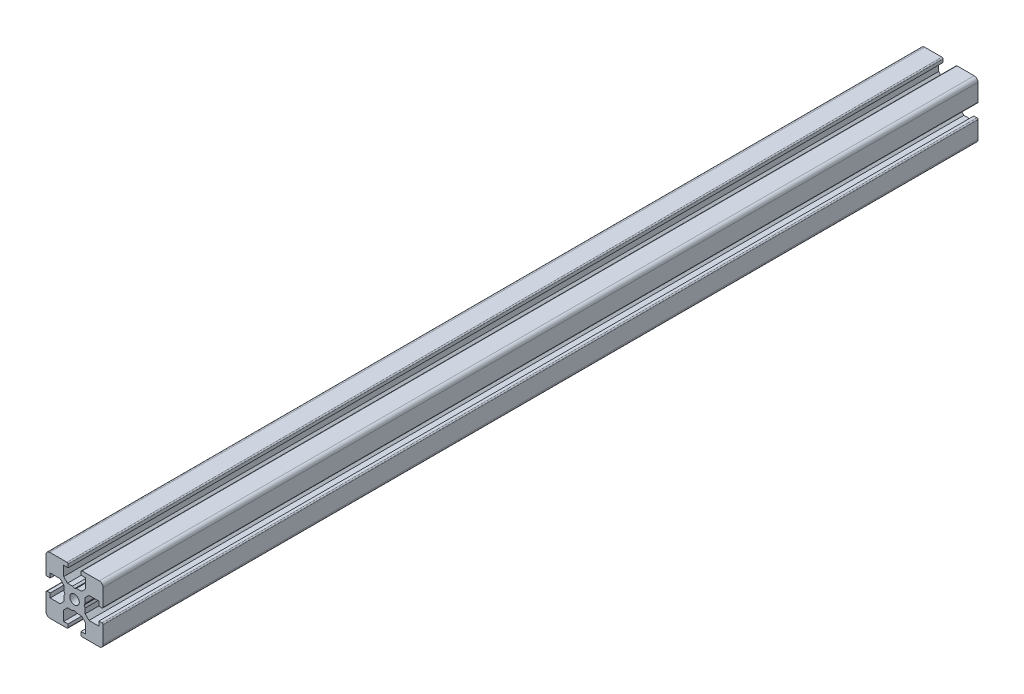
SolidWorks part; units mm, degrees
ref_plane "Front" through (0, 0, 0) normal (0, 0, 1) x (1, 0, 0)
ref_plane "Top" through (0, 0, 0) normal (0, 1, 0) x (1, 0, 0)
ref_plane "Right" through (0, 0, 0) normal (1, 0, 0) x (0, 0, -1)
ref_plane "Plane1" through (0, 0, 300) normal (0, 0, 1) x (1, 0, 0)
sketch "Sketch1" plane through (0, 0, 300) normal (0, 0, 1) x (1, 0, 0)
  line L0 (-7.5, 6.5) -> (-7.5, 2)
  line L1 (-7.2, 1.7) -> (-6.4, 1.7)
  line L2 (-6.4, 1.7) -> (-6.4, 2.85)
  line L3 (-6.4, 2.85) -> (-3.8, 2.85)
  line L4 (-3.8, 2.85) -> (-2.8, 1.85)
  line L5 (-2.8, 1.85) -> (-2.8, 0.5196)
  line L6 (-2.8, 0.5196) -> (-2.5, 0)
  line L7 (-2.5, 0) -> (-2.8, -0.5196)
  line L8 (-2.8, -0.5196) -> (-2.8, -1.85)
  line L9 (-2.8, -1.85) -> (-3.8, -2.85)
  line L10 (-3.8, -2.85) -> (-6.4, -2.85)
  line L11 (-6.4, -2.85) -> (-6.4, -1.7)
  line L12 (-6.4, -1.7) -> (-7.2, -1.7)
  line L13 (-7.5, -2) -> (-7.5, -6.5)
  line L14 (-6.5, -7.5) -> (-2, -7.5)
  line L15 (-1.7, -7.2) -> (-1.7, -6.4)
  line L16 (-1.7, -6.4) -> (-2.85, -6.4)
  line L17 (-2.85, -6.4) -> (-2.85, -3.8)
  line L18 (-2.85, -3.8) -> (-1.85, -2.8)
  line L19 (-1.85, -2.8) -> (-0.5196, -2.8)
  line L20 (-0.5196, -2.8) -> (0, -2.5)
  line L21 (0, -2.5) -> (0.5196, -2.8)
  line L22 (0.5196, -2.8) -> (1.85, -2.8)
  line L23 (1.85, -2.8) -> (2.85, -3.8)
  line L24 (2.85, -3.8) -> (2.85, -6.4)
  line L25 (2.85, -6.4) -> (1.7, -6.4)
  line L26 (1.7, -6.4) -> (1.7, -7.2)
  line L27 (2, -7.5) -> (6.5, -7.5)
  line L28 (7.5, -6.5) -> (7.5, -2)
  line L29 (7.2, -1.7) -> (6.4, -1.7)
  line L30 (6.4, -1.7) -> (6.4, -2.85)
  line L31 (6.4, -2.85) -> (3.8, -2.85)
  line L32 (3.8, -2.85) -> (2.8, -1.85)
  line L33 (2.8, -1.85) -> (2.8, -0.5196)
  line L34 (2.8, -0.5196) -> (2.5, 0)
  line L35 (2.5, 0) -> (2.8, 0.5196)
  line L36 (2.8, 0.5196) -> (2.8, 1.85)
  line L37 (2.8, 1.85) -> (3.8, 2.85)
  line L38 (3.8, 2.85) -> (6.4, 2.85)
  line L39 (6.4, 2.85) -> (6.4, 1.7)
  line L40 (6.4, 1.7) -> (7.2, 1.7)
  line L41 (7.5, 2) -> (7.5, 6.5)
  line L42 (6.5, 7.5) -> (2, 7.5)
  line L43 (1.7, 7.2) -> (1.7, 6.4)
  line L44 (1.7, 6.4) -> (2.85, 6.4)
  line L45 (2.85, 6.4) -> (2.85, 3.8)
  line L46 (2.85, 3.8) -> (1.85, 2.8)
  line L47 (1.85, 2.8) -> (0.5196, 2.8)
  line L48 (0.5196, 2.8) -> (0, 2.5)
  line L49 (0, 2.5) -> (-0.5196, 2.8)
  line L50 (-0.5196, 2.8) -> (-1.85, 2.8)
  line L51 (-1.85, 2.8) -> (-2.85, 3.8)
  line L52 (-2.85, 3.8) -> (-2.85, 6.4)
  line L53 (-2.85, 6.4) -> (-1.7, 6.4)
  line L54 (-1.7, 6.4) -> (-1.7, 7.2)
  line L55 (-2, 7.5) -> (-6.5, 7.5)
  circle A0 centre (0, 0) radius 1.25
  arc A1 (-7.5, 2) -> (-7.2, 1.7) centre (-7.2, 2) ccw
  arc A2 (-7.2, -1.7) -> (-7.5, -2) centre (-7.2, -2) ccw
  arc A3 (-7.5, -6.5) -> (-6.5, -7.5) centre (-6.5, -6.5) ccw
  arc A4 (-2, -7.5) -> (-1.7, -7.2) centre (-2, -7.2) ccw
  arc A5 (1.7, -7.2) -> (2, -7.5) centre (2, -7.2) ccw
  arc A6 (6.5, -7.5) -> (7.5, -6.5) centre (6.5, -6.5) ccw
  arc A7 (7.5, -2) -> (7.2, -1.7) centre (7.2, -2) ccw
  arc A8 (7.2, 1.7) -> (7.5, 2) centre (7.2, 2) ccw
  arc A9 (7.5, 6.5) -> (6.5, 7.5) centre (6.5, 6.5) ccw
  arc A10 (2, 7.5) -> (1.7, 7.2) centre (2, 7.2) ccw
  arc A11 (-1.7, 7.2) -> (-2, 7.5) centre (-2, 7.2) ccw
  arc A12 (-6.5, 7.5) -> (-7.5, 6.5) centre (-6.5, 6.5) ccw
extrude "Boss-Extrude1" add sketch "Sketch1" against normal blind 230
